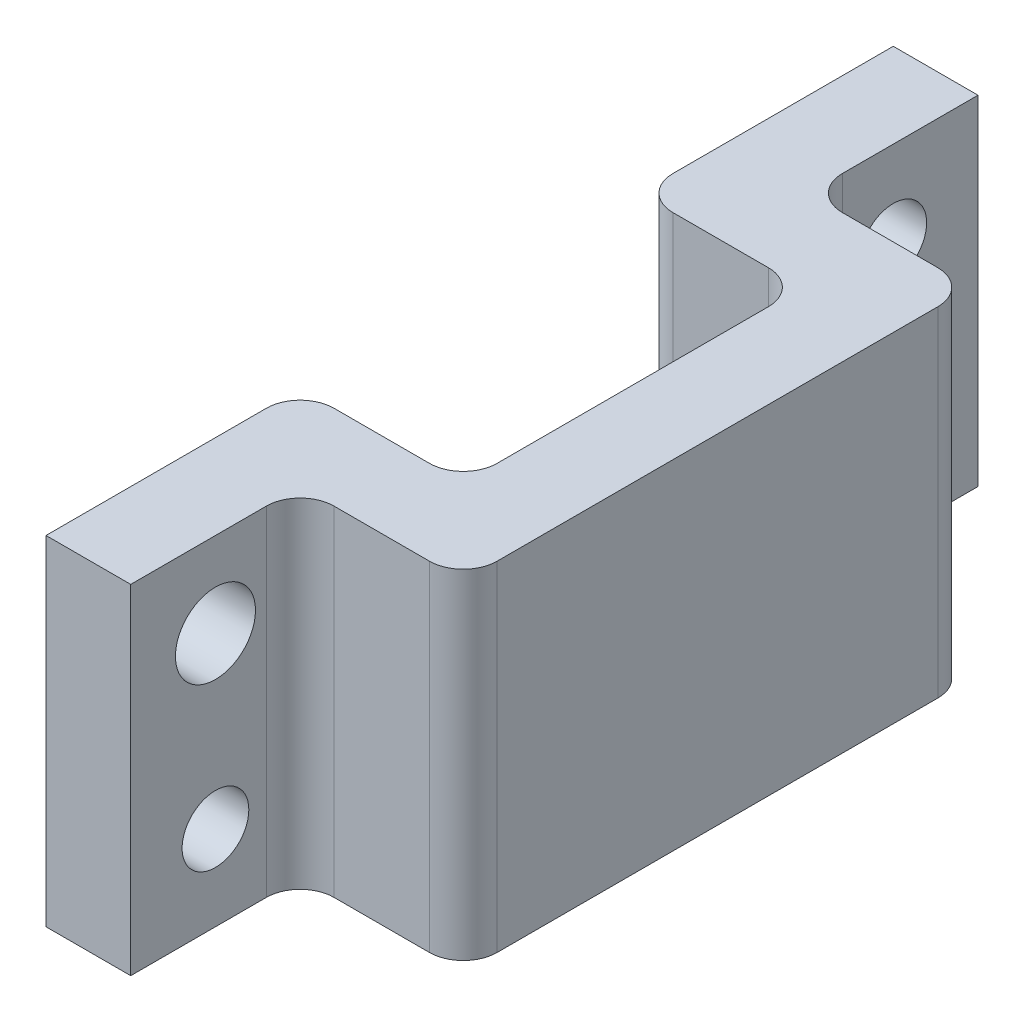
SolidWorks part; units mm, degrees
material "6061 Alloy"
ref_plane "Front Plane" through (0, 0, 0) normal (0, 0, 1) x (1, 0, 0)
ref_plane "Top Plane" through (0, 0, 0) normal (0, 1, 0) x (1, 0, 0)
ref_plane "Right Plane" through (0, 0, 0) normal (1, 0, 0) x (0, 0, -1)
sketch "Sketch1" plane through (0, 0, 0) normal (0, 1, 0) x (1, 0, 0)
  line L13 (0.4763, 31.75) -> (0.4763, 15.24)
  line L14 (-12.7, -12.7) -> (12.7, -12.7) construction
  line L39 (-12.7, 12.7) -> (12.7, 12.7) construction
  line L40 (12.7, -12.7) -> (12.7, 12.7) construction
  line L41 (0, 12.7) -> (0, -12.7) construction
  line L42 (-12.7, 0) -> (12.7, 0) construction
  line L44 (3.0163, 12.7) -> (10.16, 12.7)
  line L45 (12.7, 10.16) -> (12.7, -10.16)
  line L46 (10.16, -12.7) -> (3.0163, -12.7)
  line L47 (0.4763, -15.24) -> (0.4763, -31.75)
  line L48 (6.8262, 31.75) -> (6.8263, 21.59)
  line L49 (9.3663, 19.05) -> (16.51, 19.05)
  line L50 (19.05, 16.51) -> (19.05, -16.51)
  line L51 (16.51, -19.05) -> (9.3663, -19.05)
  line L52 (6.8263, -21.59) -> (6.8263, -31.75)
  line L53 (0.4763, 31.75) -> (6.8262, 31.75)
  line L54 (6.8263, -31.75) -> (0.4763, -31.75)
  line L55 (19.05, -19.05) -> (6.8263, -19.05) construction
  line L56 (6.8263, -19.05) -> (6.8263, -31.75) construction
  line L57 (12.7, -12.7) -> (0.4763, -12.7) construction
  line L58 (0.4763, -12.7) -> (0.4763, -31.75) construction
  line L59 (19.05, 19.05) -> (19.05, -19.05) construction
  line L60 (12.7, 12.7) -> (12.7, -12.7) construction
  line L61 (6.8262, 19.05) -> (19.05, 19.05) construction
  line L62 (0.4763, 12.7) -> (12.7, 12.7) construction
  line L63 (6.8262, 31.75) -> (6.8262, 19.05) construction
  line L64 (0.4763, 31.75) -> (0.4763, 12.7) construction
  line L77 (-12.7, 12.7) -> (-12.7, -12.7) construction
  arc A16 (9.3663, -19.05) -> (6.8263, -21.59) centre (9.3663, -21.59) ccw
  arc A17 (3.0163, -12.7) -> (0.4763, -15.24) centre (3.0163, -15.24) ccw
  arc A18 (19.05, -16.51) -> (16.51, -19.05) centre (16.51, -16.51) cw
  arc A19 (12.7, -10.16) -> (10.16, -12.7) centre (10.16, -10.16) cw
  arc A20 (16.51, 19.05) -> (19.05, 16.51) centre (16.51, 16.51) cw
  arc A21 (10.16, 12.7) -> (12.7, 10.16) centre (10.16, 10.16) cw
  arc A22 (6.8263, 21.59) -> (9.3663, 19.05) centre (9.3663, 21.59) ccw
  arc A23 (0.4763, 15.24) -> (3.0163, 12.7) centre (3.0163, 15.24) ccw
  point P0 (0, 0)
  point P20 (0.4763, -12.7)
  dimension "D5" = 2.54
  dimension "D2" = 6.35
  dimension "D1" = 25.4
  dimension "D3" = 19.05
  dimension "D4" = 0.9525
extrude "Boss-Extrude2" add sketch "Sketch1" along normal blind 25.4
sketch "Sketch2" plane through (6.8263, 0, 0) normal (1, 0, 0) x (0, 0, -1)
  line L0 (-31.75, 12.7) -> (31.75, 12.7) construction
  line L1 (-31.75, 25.4) -> (-31.75, 0) construction
  line L2 (31.75, 25.4) -> (31.75, 0) construction
  line L3 (0, 25.4) -> (0, 0) construction
  line L4 (-16.51, 25.4) -> (16.51, 25.4) construction
  line L5 (-31.75, 0) -> (-21.59, 0) construction
  circle A0 centre (-25.4, 19.05) radius 3
  circle A1 centre (25.4, 6.35) radius 3
  point P8 (-25.4, 6.35)
  point P20 (25.4, 19.05)
  dimension "D2" = 6.35
  dimension "D3" = 6.35
  dimension "D4" = 6.35
  dimension "D6" = 6.35
extrude "Cut-Extrude1" cut sketch "Sketch2" against normal up to next
sketch "Sketch5" plane through (6.8263, 0, 0) normal (1, 0, 0) x (0, 0, -1)
  point P0 (-25.4, 6.35)
  point P3 (25.4, 19.05)
hole_wizard "M6x1.0 Tapped Hole1" positions "Sketch5" profile "Sketch4" tap size "M6x1.0" standard "ANSI Metric" end condition through all
sketch "Sketch4" plane through (6.8263, 6.35, 25.4) normal (0, 1, 0) x (0, 0, -1)
  line L0 (0, 0) -> (0, 6.35)
  line L1 (0, 6.35) -> (2.5, 6.35)
  line L2 (2.5, 6.35) -> (2.5, 0)
  line L5 (2.5, 0) -> (0, 0)
  line L11 (0, -6.35) -> (0, 107.95) construction
  dimension "Thru Tap Drill Dia." = 5
  dimension "Thru Tap Drill Depth" = 6.35
cosmetic thread "Hole Thread1" parameters "D2"=6
cosmetic thread "Hole Thread2" parameters "D2"=6
equation "\"D6@Sketch2\"=\"D3@Sketch2\""
